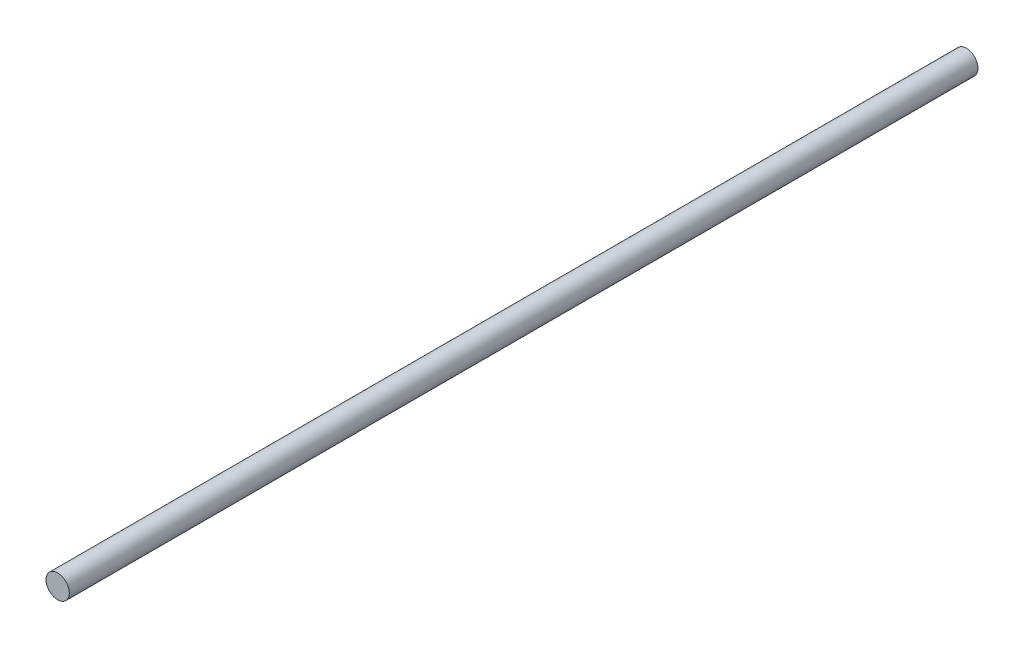
SolidWorks part; units mm, degrees
material "PVC 0.007 Plasticized"
ref_plane "Front Plane" through (0, 0, 0) normal (0, 0, 1) x (1, 0, 0)
ref_plane "Top Plane" through (0, 0, 0) normal (0, 1, 0) x (1, 0, 0)
ref_plane "Right Plane" through (0, 0, 0) normal (1, 0, 0) x (0, 0, -1)
sketch "Sketch1" plane through (0, 0, 0) normal (0, 0, 1) x (1, 0, 0)
  circle A0 centre (0, 0) radius 6
extrude "Boss-Extrude1" add sketch "Sketch1" along normal blind 468
